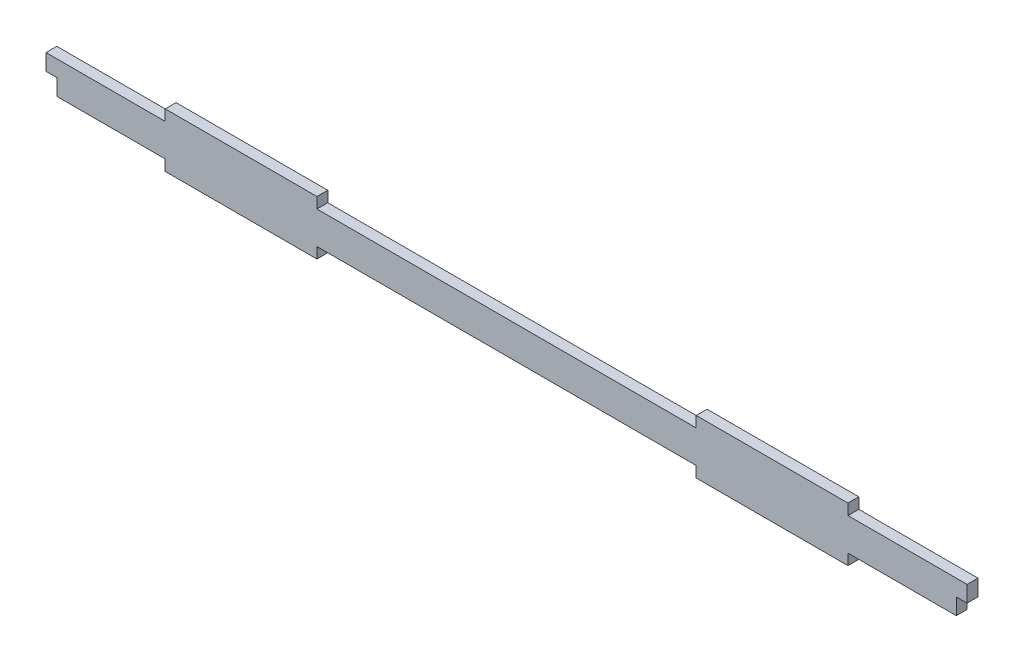
SolidWorks part; units mm, degrees
ref_plane "Front Plane" through (0, 0, 0) normal (0, 0, 1) x (1, 0, 0)
ref_plane "Top Plane" through (0, 0, 0) normal (0, 1, 0) x (1, 0, 0)
ref_plane "Right Plane" through (0, 0, 0) normal (1, 0, 0) x (0, 0, -1)
sketch "Sketch1" plane through (0, 0, 0) normal (0, 0, 1) x (1, 0, 0)
  line L1 (0, 0) -> (-415, 0)
  line L2 (0, 0) -> (0, 15)
  line L3 (0, 15) -> (-415, 15)
  line L4 (-415, 0) -> (-415, 15)
  dimension "D1" = 15
  dimension "D2" = 415
extrude "Boss-Extrude1" add sketch "Sketch1" along normal blind 5
sketch "Sketch2" plane through (0, 0, 5) normal (0, 0, 1) x (1, 0, 0)
  line L0 (-207.5, 0) -> (-207.5, 49.7222) construction
  line L1 (-415, 15) -> (-420, 15)
  line L2 (-415, 15) -> (-415, 7.5)
  line L3 (-415, 7.5) -> (-420, 7.5)
  line L4 (-420, 15) -> (-420, 7.5)
  line L5 (-415, 0) -> (0, 0) construction
  line L6 (5, 15) -> (5, 7.5)
  line L7 (0, 7.5) -> (5, 7.5)
  line L8 (0, 15) -> (0, 7.5)
  line L9 (0, 15) -> (5, 15)
  line L10 (0, 15) -> (-415, 15) construction
  line L11 (-365, 15) -> (-295, 15)
  line L12 (-365, 15) -> (-365, 20)
  line L13 (-365, 20) -> (-295, 20)
  line L14 (-295, 15) -> (-295, 20)
  line L15 (-415, 15) -> (-415, 0) construction
  line L16 (-50, 20) -> (-120, 20)
  line L17 (-120, 15) -> (-120, 20)
  line L18 (-50, 15) -> (-120, 15)
  line L19 (-50, 15) -> (-50, 20)
  line L20 (-415, 7.5) -> (-384.8143, 7.5) construction
  line L21 (-365, -5) -> (-295, -5)
  line L22 (-295, 0) -> (-295, -5)
  line L23 (-365, 0) -> (-295, 0)
  line L24 (-365, 0) -> (-365, -5)
  line L25 (-50, 0) -> (-50, -5)
  line L26 (-50, 0) -> (-120, 0)
  line L27 (-120, 0) -> (-120, -5)
  line L28 (-50, -5) -> (-120, -5)
  dimension "D1" = 5
  dimension "D2" = 7.5
  dimension "D3" = 5
  dimension "D4" = 70
  dimension "D5" = 50
extrude "Boss-Extrude2" add sketch "Sketch2" against normal blind 5
